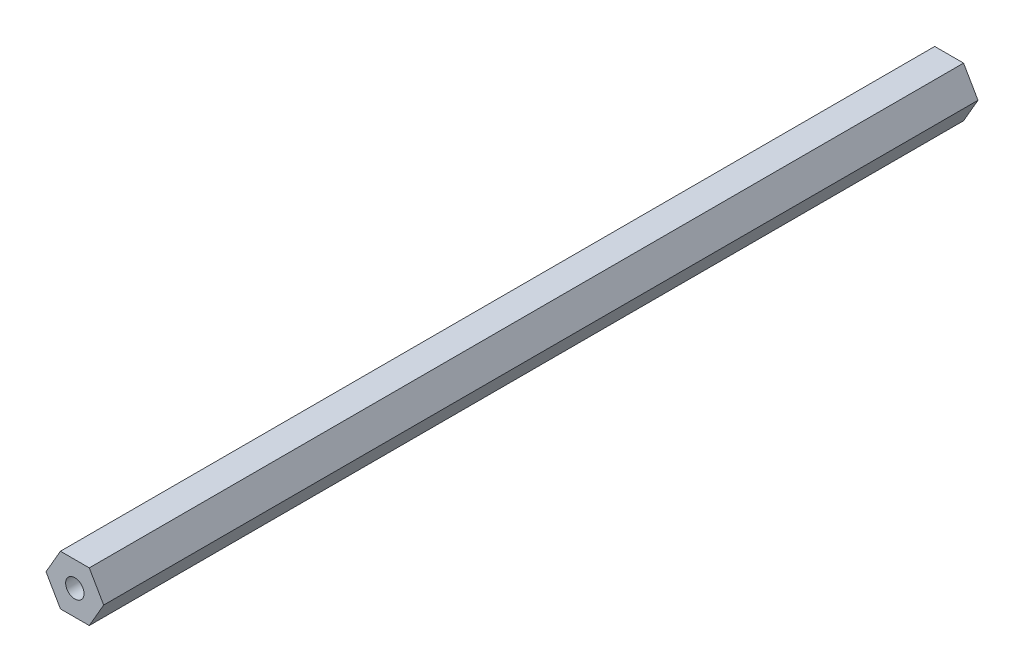
SolidWorks part; units mm, degrees
ref_plane "Ravnina Nacrt" through (0, 0, 0) normal (0, 0, 1) x (1, 0, 0)
ref_plane "Ravnina Tlocrt" through (0, 0, 0) normal (0, 1, 0) x (1, 0, 0)
ref_plane "Ravnina Bokocrt" through (0, 0, 0) normal (1, 0, 0) x (0, 0, -1)
sketch "Sketch1" plane through (0, 0, 0) normal (0, 0, 1) x (1, 0, 0)
  line L1 (2.3094, 4) -> (-2.3094, 4)
  line L2 (-2.3094, 4) -> (-4.6188, 0)
  line L3 (-4.6188, 0) -> (-2.3094, -4)
  line L4 (-2.3094, -4) -> (2.3094, -4)
  line L5 (2.3094, -4) -> (4.6188, 0)
  line L6 (4.6188, 0) -> (2.3094, 4)
  circle A0 centre (0, 0) radius 4 construction
  dimension "D1" = 8
extrude "Boss-Extrude1" add sketch "Sketch1" along normal blind 140
sketch "Sketch2" plane through (0, 0, 0) normal (0, 0, -1) x (-1, 0, 0)
  circle A0 centre (0, 0) radius 1.475
  dimension "D1" = 2.95
extrude "Cut-Extrude1" cut sketch "Sketch2" against normal blind 220
